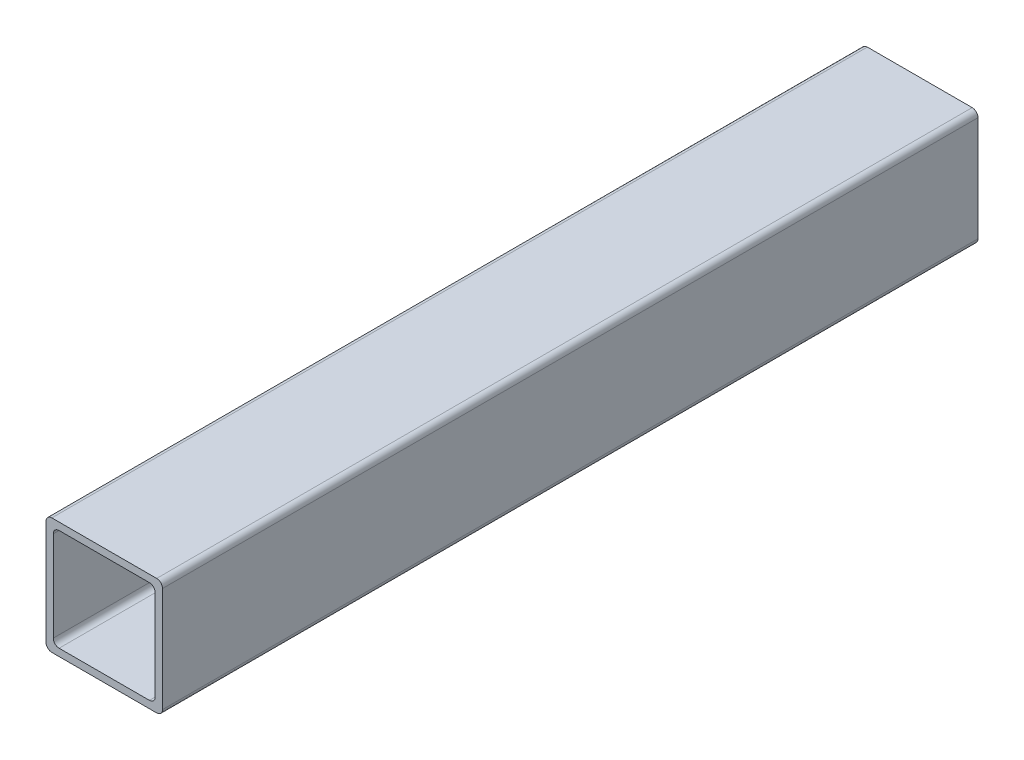
SolidWorks part; units mm, degrees
ref_plane "Front Plane" through (0, 0, 0) normal (0, 0, 1) x (1, 0, 0)
ref_plane "Top Plane" through (0, 0, 0) normal (0, 1, 0) x (1, 0, 0)
ref_plane "Right Plane" through (0, 0, 0) normal (1, 0, 0) x (0, 0, -1)
sketch "Sketch1" plane through (0, 0, 0) normal (0, 0, 1) x (1, 0, 0)
  line L0 (-19.685, 22.225) -> (19.685, 22.225)
  line L1 (-22.86, -25.4) -> (22.86, -25.4)
  line L2 (-25.4, -22.86) -> (-25.4, 22.86)
  line L3 (-22.86, 25.4) -> (22.86, 25.4)
  line L4 (25.4, -22.86) -> (25.4, 22.86)
  line L5 (-25.4, -25.4) -> (25.4, 25.4) construction
  line L6 (-25.4, 25.4) -> (25.4, -25.4) construction
  line L7 (22.225, -19.685) -> (22.225, 19.685)
  line L8 (-19.685, -22.225) -> (19.685, -22.225)
  line L9 (-22.225, -19.685) -> (-22.225, 19.685)
  line L10 (-22.225, 22.225) -> (22.225, 22.225) construction
  line L11 (22.225, -22.225) -> (22.225, 22.225) construction
  line L12 (-25.4, -25.4) -> (25.4, -25.4) construction
  line L13 (25.4, -25.4) -> (25.4, 25.4) construction
  line L14 (-22.225, -22.225) -> (22.225, -22.225) construction
  line L15 (-22.225, -22.225) -> (-22.225, 22.225) construction
  line L16 (-25.4, -25.4) -> (-25.4, 25.4) construction
  line L17 (-25.4, 25.4) -> (25.4, 25.4) construction
  arc A0 (19.685, 22.225) -> (22.225, 19.685) centre (19.685, 19.685) cw
  arc A1 (22.86, -25.4) -> (25.4, -22.86) centre (22.86, -22.86) ccw
  arc A2 (22.225, -19.685) -> (19.685, -22.225) centre (19.685, -19.685) cw
  arc A3 (-19.685, -22.225) -> (-22.225, -19.685) centre (-19.685, -19.685) cw
  arc A4 (-22.86, -25.4) -> (-25.4, -22.86) centre (-22.86, -22.86) cw
  arc A5 (22.86, 25.4) -> (25.4, 22.86) centre (22.86, 22.86) cw
  arc A6 (-19.685, 22.225) -> (-22.225, 19.685) centre (-19.685, 19.685) ccw
  arc A7 (-25.4, 22.86) -> (-22.86, 25.4) centre (-22.86, 22.86) cw
  point P0 (0, 0)
  dimension "D4" = 2.54
  dimension "D1" = 50.8
  dimension "D2" = 50.8
  dimension "D3" = 3.175
extrude "Boss-Extrude1" add sketch "Sketch1" along normal mid plane 355.6
